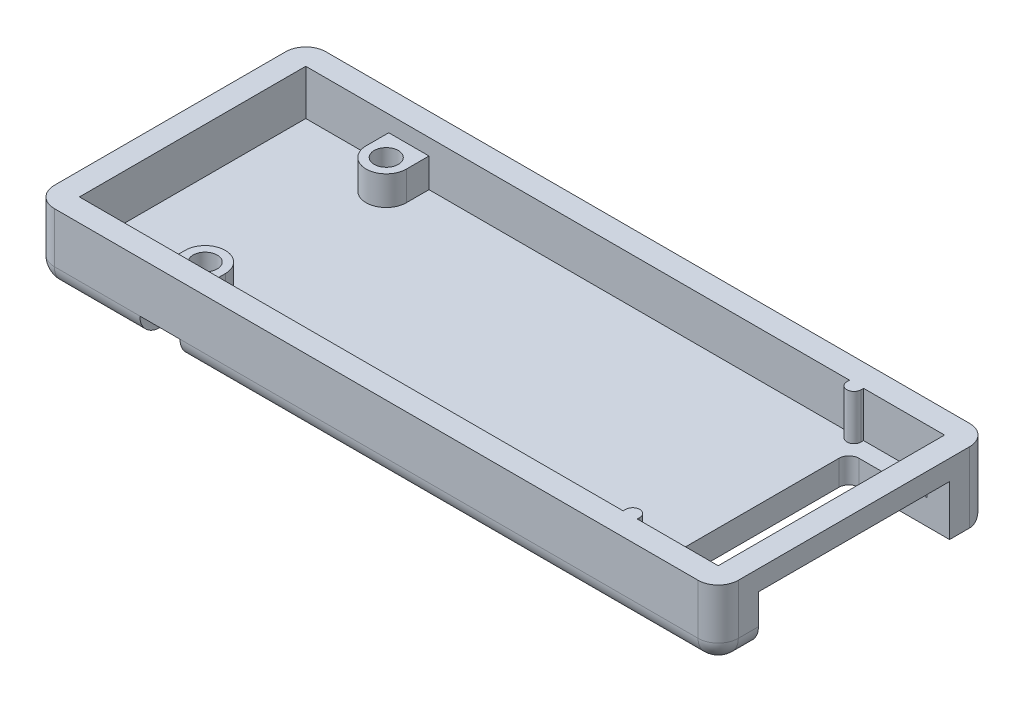
SolidWorks part; units mm, degrees
ref_plane "Спереди" through (0, 0, 0) normal (0, 0, 1) x (1, 0, 0)
ref_plane "Сверху" through (0, 0, 0) normal (0, 1, 0) x (1, 0, 0)
ref_plane "Справа" through (0, 0, 0) normal (1, 0, 0) x (0, 0, -1)
sketch "Эскиз1" plane through (0, 0, 0) normal (0, 1, 0) x (1, 0, 0)
  line L1 (-34, 13.5) -> (34, 13.5)
  line L2 (-34, 13.5) -> (-34, -13.5)
  line L3 (-34, -13.5) -> (34, -13.5)
  line L4 (34, 13.5) -> (34, -13.5)
  line L5 (-34, 13.5) -> (34, -13.5) construction
  line L6 (-34, -13.5) -> (34, 13.5) construction
  point P0 (0, 0)
  dimension "D1" = 27
  dimension "D2" = 68
extrude "Бобышка-Вытянуть1" add sketch "Эскиз1" along normal blind 7
sketch "Эскиз2" plane through (0, 7, 0) normal (0, 1, 0) x (1, 0, 0)
  line L1 (-31.75, -11.25) -> (31.75, -11.25)
  line L2 (-31.75, -11.25) -> (-31.75, 11.25)
  line L3 (-31.75, 11.25) -> (31.75, 11.25)
  line L4 (31.75, -11.25) -> (31.75, 11.25)
  line L5 (-31.75, -11.25) -> (31.75, 11.25) construction
  line L6 (-31.75, 11.25) -> (31.75, -11.25) construction
  point P0 (0, 0)
  dimension "D1" = 22.5
  dimension "D2" = 63.5
extrude "Вырез-Вытянуть1" cut sketch "Эскиз2" against normal offset from surface (4.5 mm away) 2.5 up to face at (0, 0, 0)
sketch "Эскиз3" plane through (0, 2.5, 0) normal (0, 1, 0) x (1, 0, 0)
  line L0 (-21.5, 9) -> (-21.5, -9) construction
  line L1 (0, 0) -> (-38.0789, 0) construction
  line L2 (-23.5, 9) -> (-23.5, 11.25)
  line L3 (31.75, 11.25) -> (-31.75, 11.25) construction
  line L4 (-23.5, 11.25) -> (-19.5, 11.25)
  line L5 (-19.5, 11.25) -> (-19.5, 9)
  line L6 (-19.5, -11.25) -> (-19.5, -9)
  line L7 (-23.5, -11.25) -> (-19.5, -11.25)
  line L8 (-23.5, -9) -> (-23.5, -11.25)
  arc A0 (-19.5, 9) -> (-23.5, 9) centre (-21.5, 9) cw
  arc A1 (-19.5, -9) -> (-23.5, -9) centre (-21.5, -9) ccw
  point P5 (-21.5, 0)
  dimension "D3" = 2
  dimension "D1" = 21.5
  dimension "D2" = 18
extrude "Бобышка-Вытянуть2" add sketch "Эскиз3" along normal offset from surface (2.9 mm away) 1.6 up to face at (0, 7, 0)
sketch "Эскиз4" plane through (0, 2.5, 0) normal (0, 1, 0) x (1, 0, 0)
  line L0 (0, 0) -> (49.7273, 0) construction
  line L1 (23, 11) -> (23, -11) construction
  line L2 (22.3, 11) -> (22.3, 11.25)
  line L3 (-19.5, 11.25) -> (31.75, 11.25) construction
  line L4 (22.3, 11.25) -> (23.7, 11.25)
  line L5 (23.7, 11.25) -> (23.7, 11)
  line L6 (23.7, -11.25) -> (23.7, -11)
  line L7 (22.3, -11.25) -> (23.7, -11.25)
  line L8 (22.3, -11) -> (22.3, -11.25)
  arc A0 (22.3, 11) -> (23.7, 11) centre (23, 11) ccw
  arc A1 (22.3, -11) -> (23.7, -11) centre (23, -11) cw
  point P5 (23, 0)
  dimension "D3" = 0.7
  dimension "D1" = 23
  dimension "D2" = 22
extrude "Бобышка-Вытянуть3" add sketch "Эскиз4" along normal up to surface (4.5 mm away) up to face at (0, 7, 0)
sketch "Эскиз5" plane through (0, 5.4, 0) normal (0, 1, 0) x (1, 0, 0)
  line L0 (0, 0) -> (-40.9424, 0) construction
  circle A0 centre (-21.5, 9) radius 1.2
  circle A1 centre (-21.5, -9) radius 1.2
  dimension "D1" = 2.4
extrude "Вырез-Вытянуть2" cut sketch "Эскиз5" against normal through all
sketch "Эскиз6" plane through (0, 0, 0) normal (0, -1, 0) x (1, 0, 0)
  line L0 (0, 0) -> (-42.8446, 0) construction
  line L1 (-19.5, -9) -> (-19.5, -13.5)
  line L2 (34, -13.5) -> (-34, -13.5) construction
  line L3 (-19.5, -13.5) -> (-23.5, -13.5)
  line L4 (-23.5, -13.5) -> (-23.5, -9)
  line L5 (-23.5, 13.5) -> (-23.5, 9)
  line L6 (-19.5, 13.5) -> (-23.5, 13.5)
  line L7 (-19.5, 9) -> (-19.5, 13.5)
  arc A0 (-19.5, -9) -> (-23.5, -9) centre (-21.5, -9) ccw
  arc A1 (-19.5, 9) -> (-23.5, 9) centre (-21.5, 9) cw
  dimension "D1" = 2
extrude "Вырез-Вытянуть3" cut sketch "Эскиз6" against normal blind 2
sketch "Эскиз7" plane through (0, 0, 0) normal (0, -1, 0) x (1, 0, 0)
  line L0 (34, 0) -> (16.0425, 0) construction
  line L1 (34, 13.5) -> (34, -13.5) construction
  line L3 (24, 9.5) -> (34, 9.5)
  line L4 (24, 9.5) -> (24, -9.5)
  line L5 (24, -9.5) -> (34, -9.5)
  line L6 (34, 9.5) -> (34, -9.5)
  line L7 (24, 9.5) -> (34, -9.5) construction
  line L8 (24, -9.5) -> (34, 9.5) construction
  point P5 (29, 0)
  dimension "D1" = 10
  dimension "D2" = 19
extrude "Вырез-Вытянуть4" cut sketch "Эскиз7" against normal blind 5
fillet "Скругление1" radius 2 13 edges at (-23.5, 1, -13.5) (-23.5, 1, 13.5) (-19.5, 1, 13.5) (-28.75, 0, 13.5) (-34, 0, 0) (7.25, 0, -13.5) (34, 3.5, 13.5) (-34, 3.5, 13.5) (-34, 3.5, -13.5) (34, 3.5, -13.5) (7.25, 0, 13.5) (-28.75, 0, -13.5) (-19.5, 1, -13.5)
fillet "Скругление2" radius 1 2 edges at (24, 1.25, -9.5) (24, 1.25, 9.5)
